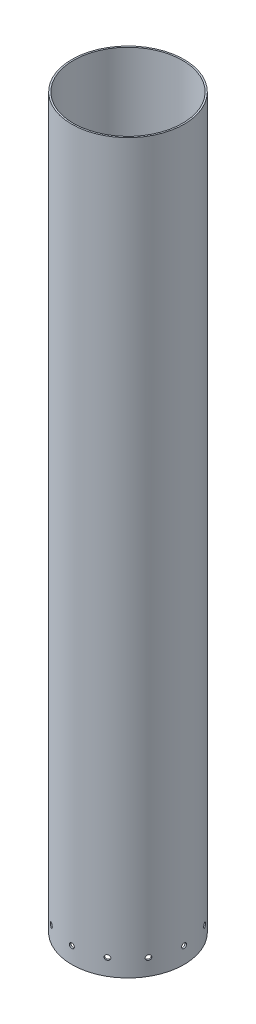
SolidWorks part; units mm, degrees
material "A-Glass Fiber"
ref_plane "Front Plane" through (0, 0, 0) normal (0, 0, 1) x (1, 0, 0)
ref_plane "Top Plane" through (0, 0, 0) normal (0, 1, 0) x (1, 0, 0)
ref_plane "Right Plane" through (0, 0, 0) normal (1, 0, 0) x (0, 0, -1)
sketch "Sketch1" plane through (0, 0, 0) normal (0, 1, 0) x (1, 0, 0)
  circle A0 centre (0, 0) radius 78.359
  circle A1 centre (0, 0) radius 76.2
  dimension "D1" = 152.4
  dimension "D2" = 156.718
extrude "Boss-Extrude1" add sketch "Sketch1" along normal blind 1016
ref_plane "Plane1" through (0, 0, 78.359) normal (0, 0, 1) x (1, 0, 0)
sketch "Sketch2" plane through (0, 0, 78.359) normal (0, 0, 1) x (1, 0, 0)
  line L0 (-78.359, 0) -> (78.359, 0) construction
  line L1 (-78.359, 0) -> (78.359, 0) construction
  line L2 (0, 0) -> (0, 1016) construction
  line L3 (78.359, 1016) -> (-78.359, 1016) construction
  line L4 (78.359, 1016) -> (-78.359, 1016) construction
  circle A0 centre (0, 22.86) radius 3.429
  dimension "D1" = 6.858
  dimension "D2" = 22.86
extrude "Cut-Extrude1" cut sketch "Sketch2" against normal up to next
pattern_circular "CirPattern1" count 12 over 360 about axis through (0, 0, 0) along (0, 1, 0) of "Cut-Extrude1"
